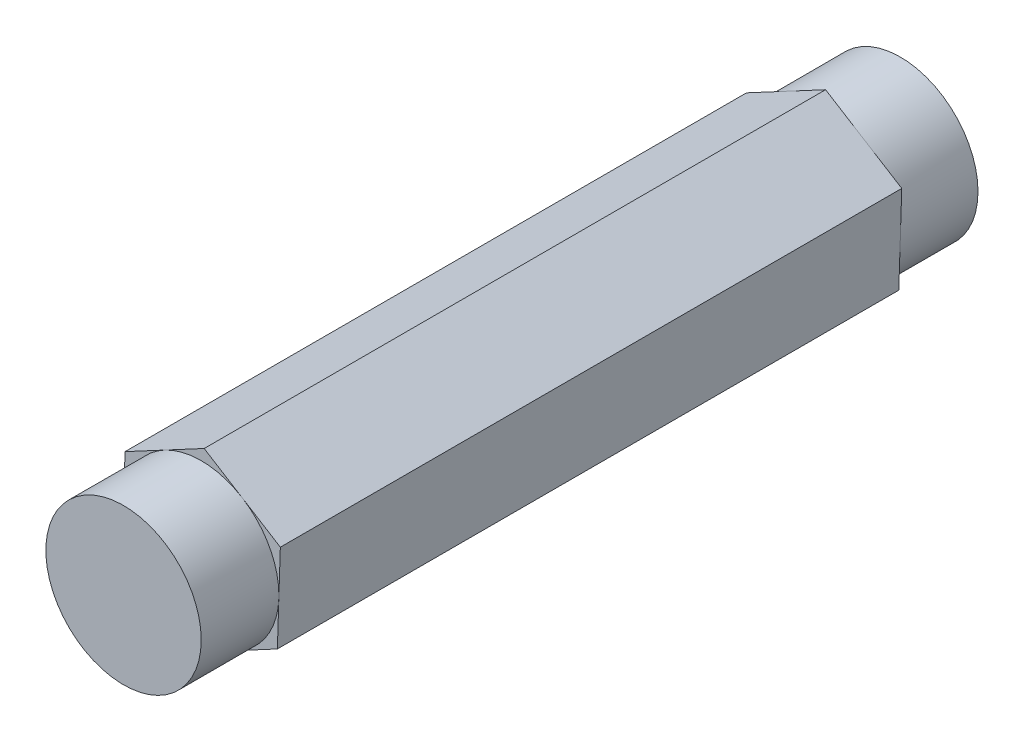
SolidWorks part; units mm, degrees
ref_plane "Front Plane" through (0, 0, 0) normal (0, 0, 1) x (1, 0, 0)
ref_plane "Top Plane" through (0, 0, 0) normal (0, 1, 0) x (1, 0, 0)
ref_plane "Right Plane" through (0, 0, 0) normal (1, 0, 0) x (0, 0, -1)
sketch "Sketch1" plane through (0, 0, 0) normal (0, 0, 1) x (1, 0, 0)
  line L1 (-0.2451, 0.1525) -> (-0.2546, -0.136)
  line L2 (-0.2546, -0.136) -> (-0.0095, -0.2885)
  line L3 (-0.0095, -0.2885) -> (0.2451, -0.1525)
  line L4 (0.2451, -0.1525) -> (0.2546, 0.136)
  line L5 (0.2546, 0.136) -> (0.0095, 0.2885)
  line L6 (0.0095, 0.2885) -> (-0.2451, 0.1525)
  circle A0 centre (0, 0) radius 0.25 construction
  point P1 (0, 0)
  dimension "D1" = 0.5
extrude "Boss-Extrude1" add sketch "Sketch1" along normal blind 2
sketch "Sketch2" plane through (0, 0, 2) normal (0, 0, 1) x (1, 0, 0)
  circle A0 centre (0, 0) radius 0.25
extrude "Boss-Extrude2" add sketch "Sketch2" along normal blind 0.25 and the other way offset from surface (2.25 mm away) 0.25 other way up to face at (0, 0, 0)
